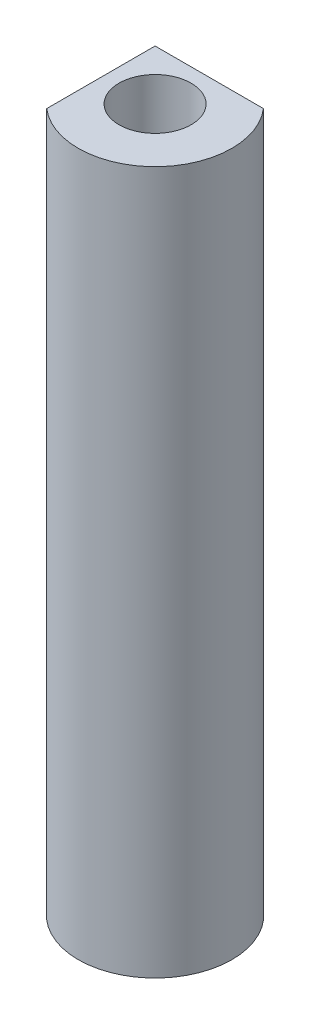
SolidWorks part; units mm, degrees
ref_plane "Front Plane" through (0, 0, 0) normal (0, 0, 1) x (1, 0, 0)
ref_plane "Top Plane" through (0, 0, 0) normal (0, 1, 0) x (1, 0, 0)
ref_plane "Right Plane" through (0, 0, 0) normal (1, 0, 0) x (0, 0, -1)
sketch "Sketch1" plane through (0, 0, 0) normal (0, 1, 0) x (1, 0, 0)
  circle A0 centre (0, 0) radius 4.9
  circle A1 centre (0, 0) radius 2.3
  dimension "D1" = 9.8
  dimension "D2" = 4.6
extrude "Boss-Extrude1" add sketch "Sketch1" along normal blind 44.8
sketch "Sketch2" plane through (0, 44.8, 0) normal (0, 1, 0) x (1, 0, 0)
  line L1 (-5.554, 3.2) -> (7.3578, 3.2)
  line L2 (-5.554, 3.2) -> (-5.554, 6.0714)
  line L3 (-5.554, 6.0714) -> (7.3578, 6.0714)
  line L4 (7.3578, 3.2) -> (7.3578, 6.0714)
  circle A0 centre (0, 0) radius 2.3 construction
  dimension "D1" = 3.2
extrude "Cut-Extrude1" cut sketch "Sketch2" against normal blind 45
sketch "Sketch3" plane through (0, 44.8, 0) normal (0, 1, 0) x (1, 0, 0)
  line L1 (-20.8712, -5.7993) -> (-3.2, -5.7993)
  line L2 (-20.8712, -5.7993) -> (-20.8712, 14.2007)
  line L3 (-20.8712, 14.2007) -> (-3.2, 14.2007)
  line L4 (-3.2, -5.7993) -> (-3.2, 14.2007)
  circle A1 centre (0, 0) radius 2.3 construction
  dimension "D1" = 20
  dimension "D2" = 3.2
extrude "Cut-Extrude2" cut sketch "Sketch3" against normal blind 40
